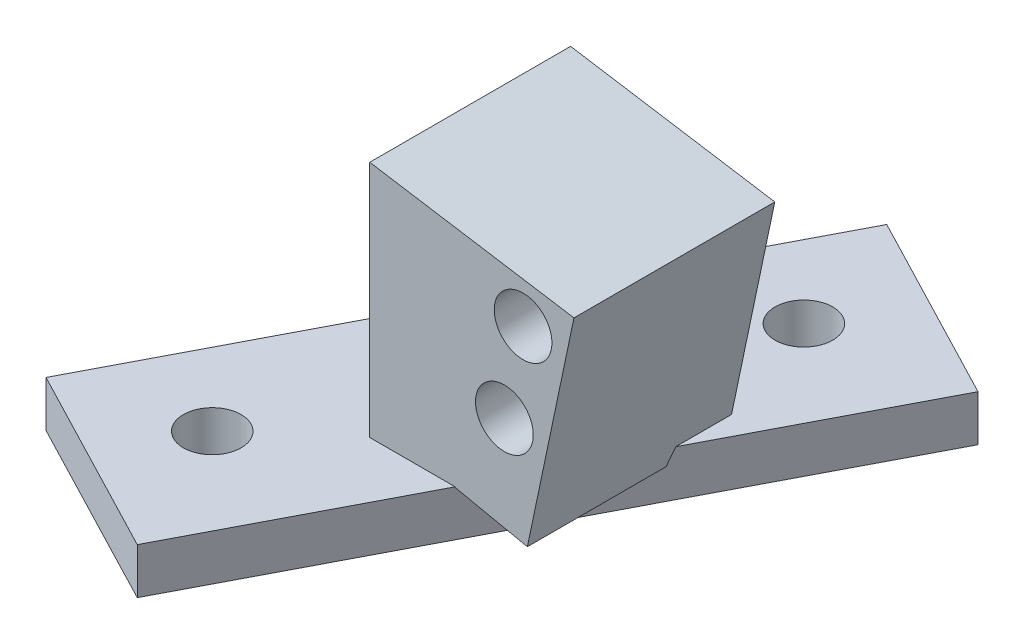
SolidWorks part; units mm, degrees
ref_plane "Front Plane" through (0, 0, 0) normal (0, 0, 1) x (1, 0, 0)
ref_plane "Top Plane" through (0, 0, 0) normal (0, 1, 0) x (1, 0, 0)
ref_plane "Right Plane" through (0, 0, 0) normal (1, 0, 0) x (0, 0, -1)
sketch "Sketch2" plane through (0, 0, 0) normal (0, 0, 1) x (1, 0, 0)
  line L0 (-629.4563, 228.6083) -> (-646.4173, 232.1744)
  line L1 (-626.309, 227.9466) -> (-640.2031, 230.8679) construction
  line L2 (-646.4173, 232.1744) -> (-650.3578, 213.4325)
  line L3 (-650.3578, 213.4325) -> (-633.3967, 209.8665)
  line L4 (-627.1923, 208.562) -> (-644.038, 212.1038) construction
  line L5 (-633.3967, 209.8665) -> (-629.4563, 228.6083)
  circle A0 centre (-637.1112, 215.214) radius 3.175 construction
  circle A1 centre (-635.0536, 225) radius 3.175 construction
  circle A2 centre (-637.1112, 215.214) radius 3.175
  circle A3 centre (-635.0536, 225) radius 3.175
  circle A4 centre (-637.1112, 215.214) radius 3.175
  circle A5 centre (-635.0536, 225) radius 3.175
  circle M5 centre (-637.1112, 215.214) radius 3.175
  line M6 (-610.5669, 224.6368) -> (-640.2031, 230.8679)
  arc M7 (-640.2031, 230.8679) -> (-641.8455, 221.1503) centre (-635.0536, 225) ccw
  arc M8 (-641.8455, 221.1503) -> (-644.038, 212.1038) centre (-637.1112, 215.214) ccw
  line M9 (-644.038, 212.1038) -> (-609.6489, 204.8735)
  circle M13 centre (-635.0536, 225) radius 3.175
  dimension "D1" = 19.1516
  dimension "D2" = 17.3318
  dimension "D3" = 6.35
extrude "Boss-Extrude1" add sketch "Sketch2" along normal up to surface (2953.4037 mm away) contours L5 M9 M6 M7 M8 M13 M5 | L2 L3 L0 M8 M7
sketch "Sketch3" plane through (15.4424, 73.4471, 0) normal (-0.2058, -0.9786, 0) x (0.9786, -0.2058, 0)
  line L1 (-680.3571, 22.098) -> (-671.4671, 22.098)
  line L2 (-663.0252, 22.098) -> (-680.3571, 22.098) construction
  line L3 (-671.4671, 22.098) -> (-671.4671, 0)
  line L5 (-680.3571, 0) -> (-680.3571, 22.098)
  line L6 (-680.3571, 0) -> (-663.0252, 0) construction
  line L7 (-671.4671, 0) -> (-680.3571, 0)
  dimension "D1" = 8.89
extrude "Boss-Extrude2" add sketch "Sketch3" along normal blind 7.62 contours L7 L5 L1 L3
ref_plane "Plane1" through (0, 205.9756, 0) normal (0, 1, 0) x (1, 0, 0)
sketch "Sketch4" plane through (0, 205.9756, 0) normal (0, 1, 0) x (1, 0, 0)
  line L0 (-643.7809, 26.64) -> (-675.4552, -34.1873)
  line L1 (-675.4552, -34.1873) -> (-654.5036, -45.0973)
  line L2 (-654.5036, -45.0973) -> (-622.8293, 15.73)
  line L3 (-622.8293, 15.73) -> (-643.7809, 26.64)
  circle A0 centre (-638.8988, 12.6428) radius 3.175
  circle A1 centre (-661.1881, -30.1616) radius 3.175
  dimension "D5" = 10.16
  dimension "D9" = 6.35
  dimension "D10" = 6.35
  dimension "D1" = 68.58
  dimension "D2" = 21.59
  dimension "D3" = 5.08
  dimension "D4" = 23.622
  dimension "D6" = 10.16
  dimension "D7" = 10.795
  dimension "D8" = 10.795
  dimension "D11" = 27.3901
extrude "Boss-Extrude3" add sketch "Sketch4" against normal blind 5.0531
sketch "Sketch5" plane through (0, 0, 22.098) normal (0, 0, 1) x (1, 0, 0)
  line L0 (-651.9256, 205.9756) -> (-651.9256, 232.1994)
  line L1 (-651.9256, 232.1994) -> (-646.4173, 232.1744)
  line L2 (-646.4173, 232.1744) -> (-651.9256, 205.9756)
extrude "Boss-Extrude4" add sketch "Sketch5" against normal up to surface (22.098 mm away) up to face at (-631.8786, 225, 0)
sketch "Sketch6" plane through (0, 0, 0) normal (0, 0, -1) x (-1, 0, 0)
  line L0 (629.4563, 228.6083) -> (651.9256, 232.1994)
  line L1 (651.9256, 232.1994) -> (646.4173, 232.1744)
  line L2 (646.4173, 232.1744) -> (629.4563, 228.6083)
extrude "Cut-Extrude1" cut sketch "Sketch6" against normal blind 126.746
sketch "Sketch8" plane through (-648.8391, 136.4193, 0) normal (0.9786, -0.2058, 0) x (0, 0, -1)
  line L4 (-22.098, 69.3021) -> (0, 69.3021)
  line L5 (0, 69.3021) -> (0, 75.053)
  line L6 (0, 75.053) -> (-22.098, 75.053)
  line L7 (-22.098, 75.053) -> (-22.098, 69.3021)
  line L8 (-22.098, 69.3021) -> (0, 69.3021)
  line L9 (0, 69.3021) -> (0, 75.053)
  line L10 (0, 75.053) -> (-22.098, 75.053)
  line L11 (-22.098, 75.053) -> (-22.098, 69.3021)
  dimension "D1" = 0
extrude "Boss-Extrude6" add sketch "Sketch8" against normal up to surface (8.4418 mm away) up to face at (-642.2496, 208.7895, 11.049)
